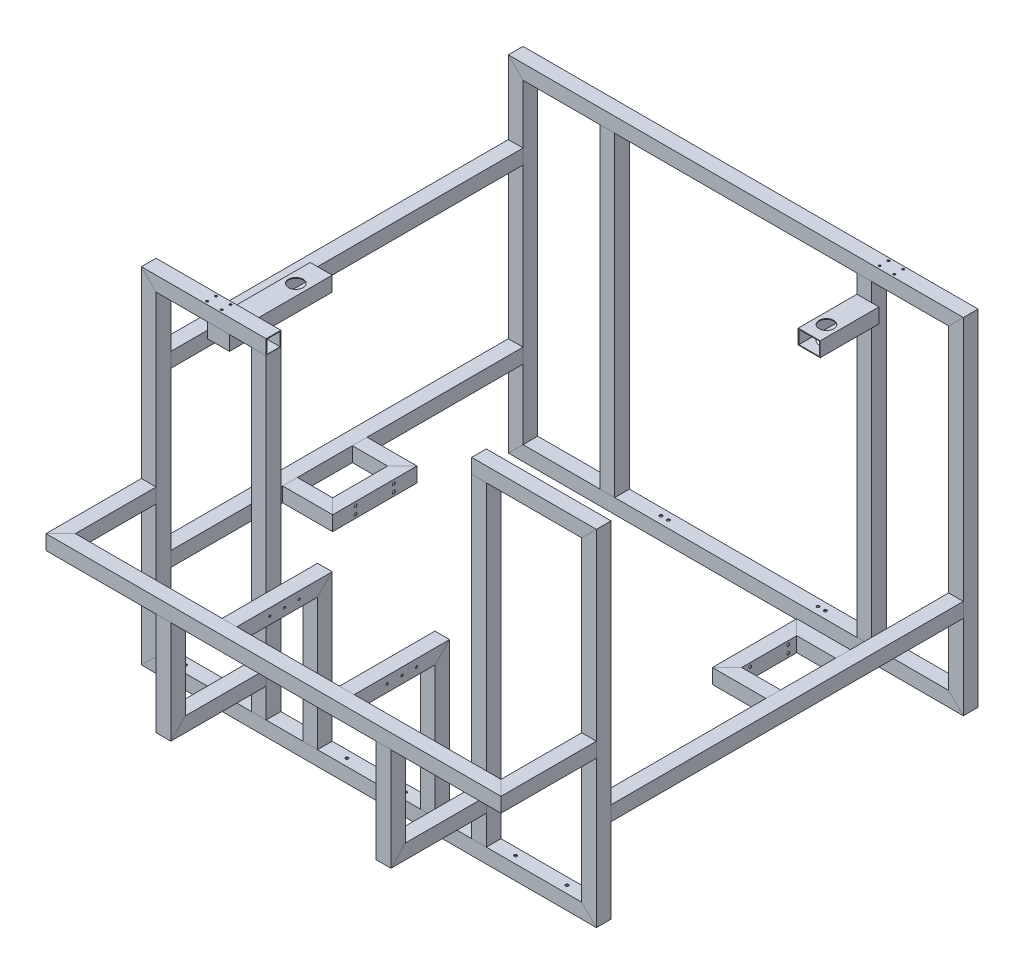
SolidWorks part; units mm, degrees
material "6063-O"
ref_plane "前视基准面" through (0, 0, 0) normal (0, 0, 1) x (1, 0, 0)
ref_plane "上视基准面" through (0, 0, 0) normal (0, 1, 0) x (1, 0, 0)
ref_plane "右视基准面" through (0, 0, 0) normal (1, 0, 0) x (0, 0, -1)
sketch "草图1" plane through (0, 0, 0) normal (0, 0, 1) x (1, 0, 0)
  line L1 (-300, 225) -> (300, 225)
  line L2 (-175, 225) -> (-175, -225)
  line L4 (175, 225) -> (175, -225)
  line L5 (-175, 225) -> (175, -225) construction
  line L6 (-175, -225) -> (175, 225) construction
  line L7 (-300, 225) -> (-300, -225)
  line L10 (300, 225) -> (300, -225)
  line L12 (-300, -225) -> (300, -225)
  point P0 (0, 0)
  dimension "D1" = 350
  dimension "D2" = 450
  dimension "D3" = 125
  dimension "D4" = 125
ref_plane "基准面1" through (0, 0, 500) normal (0, 0, 1) x (1, 0, 0)
sketch "草图2" plane through (0, 0, 500) normal (0, 0, 1) x (1, 0, 0)
  line L2 (300, 225) -> (300, -225) construction
  line L5 (-300, -225) -> (300, -225) construction
  line L6 (-300, 225) -> (-300, -225) construction
  line L7 (-150, 225) -> (-150, -225)
  line L8 (150, 225) -> (150, -225)
  line L14 (-300, 225) -> (300, 225) construction
  line L15 (300, 225) -> (300, -225)
  line L19 (-300, -225) -> (300, -225)
  line L20 (-300, 225) -> (-300, -225)
  line L22 (-300, 225) -> (300, 225)
  dimension "D1" = 150
  dimension "D2" = 150
sketch3d "3D草图1"
  line L0 (-300, -110, 0) -> (-300, -110, 500)
  line L1 (-300, 225, 0) -> (-300, -225, 0) construction
  line L2 (-300, 225, 500) -> (-300, -225, 500) construction
  line L3 (-300, 125, 0) -> (-300, 125, 500)
  line L4 (300, -110, 0) -> (300, -110, 500)
  line L5 (300, 225, 0) -> (300, -225, 0) construction
  line L6 (300, 225, 500) -> (300, -225, 500) construction
  line L8 (-300, -225, 500) -> (300, -225, 500) construction
  line L9 (300, -110, 249) -> (227, -110, 249)
  line L10 (-80, -225, 500) -> (-80, -25, 500)
  line L11 (227, -110, 249) -> (227, -110, 154)
  line L12 (80, -225, 500) -> (80, -25, 500)
  line L13 (227, -110, 154) -> (300, -110, 154)
  line L14 (-300, -110, 327.5) -> (-232, -110, 327.5)
  line L15 (-232, -110, 327.5) -> (-232, -110, 232.5)
  line L16 (-300, -25, 500) -> (-300, -25, 630)
  line L17 (-300, -25, 630) -> (300, -25, 630)
  line L18 (300, -25, 630) -> (300, -25, 500)
  line L19 (-232, -110, 232.5) -> (-300, -110, 232.5)
  line L20 (-80, -25, 630) -> (-80, -25, 500)
  line L21 (80, -25, 630) -> (80, -25, 500)
  dimension "D1" = 115
  dimension "D2" = 100
  dimension "D3" = 115
  dimension "D4" = 154
  dimension "D5" = 249
  dimension "D10" = 267.5
  dimension "D6" = 200
  dimension "D7" = 130
  dimension "D8" = 73
  dimension "D9" = 172.5
  dimension "D11" = 68
  dimension "D12" = 220
  dimension "D13" = 220
other " C:\\PROGRAM FILES\\SOLIDWORKS CORP\\SOLIDWORKS\\LANG\\CHINESE-SIMPLIFIED\\WELDMENT PROFILES\\HITCRT\\新建文件夹\\20X20X1 - 丢失(1)"
ref_plane "基准面2" through (-300, 225, 0) normal (0, -1, 0) x (1, 0, 0)
sketch "草图11" plane through (-300, 225, 0) normal (0, -1, 0) x (1, 0, 0)
  line L1 (-10, -10) -> (10, -10)
  line L2 (-10, -10) -> (-10, 10)
  line L3 (-10, 10) -> (10, 10)
  line L4 (10, -10) -> (10, 10)
  line L5 (-10, -10) -> (10, 10) construction
  line L6 (-10, 10) -> (10, -10) construction
  line L7 (-9, -9) -> (9, -9)
  line L8 (-9, -9) -> (-9, 9)
  line L9 (-9, 9) -> (9, 9)
  line L10 (9, -9) -> (9, 9)
  line L11 (-9, -9) -> (9, 9) construction
  line L12 (-9, 9) -> (9, -9) construction
  point P0 (0, 0)
  point P6 (0, 0)
  point P11 (0, 0)
  dimension "D1" = 20
  dimension "D2" = 20
  dimension "D3" = 18
  dimension "D4" = 18
sketch "草图13" plane through (0, 0, 510) normal (0, 0, 1) x (1, 0, 0)
  line L0 (-310, 235) -> (310, 235) construction
  line L1 (-140, 215) -> (140, 215)
  line L3 (-140, 235) -> (140, 235)
  line L4 (140, 215) -> (140, 235)
  line L5 (-140, 215) -> (-140, 235)
  line L7 (-140, -215) -> (-140, 215) construction
  line L8 (140, -215) -> (140, 215) construction
  dimension "D1" = 0
  dimension "D2" = 0
extrude "切除-拉伸2" cut sketch "草图13" against normal blind 20
sketch "草图14" plane through (-70, 0, 0) normal (1, 0, 0) x (0, 0, -1)
  circle A0 centre (-535, -25) radius 1.5 construction
  circle A1 centre (-555, -25) radius 1.5 construction
  circle A2 centre (-575, -25) radius 1.5 construction
  circle A3 centre (-535, -25) radius 1.5
  circle A4 centre (-555, -25) radius 1.5
  circle A5 centre (-575, -25) radius 1.5
extrude "切除-拉伸3" cut sketch "草图14" against normal blind 20 and the other way blind 230
sketch "草图17" plane through (0, 0, 510) normal (0, 0, 1) x (1, 0, 0)
  line L0 (-290, 215) -> (-140, 215) construction
  line L1 (-190, 215) -> (-220, 215)
  line L2 (-190, 215) -> (-190, 195)
  line L3 (-190, 195) -> (-220, 195)
  line L4 (-220, 215) -> (-220, 195)
  dimension "D1" = 20
  dimension "D2" = 30
extrude "凸台-拉伸3" add sketch "草图17" against normal blind 140 separate body
shell "抽壳1" thickness 1
sketch "草图18" plane through (0, 215, 0) normal (0, 1, 0) x (1, 0, 0)
  circle A0 centre (-205, -404.5) radius 10
  dimension "D1" = 20
extrude "切除-拉伸4" cut sketch "草图18" against normal up to surface (20 mm away) up to face at (-205, 195, 440)
sketch "草图19" plane through (165, 0, 0) normal (-1, 0, 0) x (0, 0, 1)
  line L0 (10, -215) -> (10, 215) construction
  line L1 (10, 190) -> (90, 190)
  line L2 (10, 190) -> (10, 170)
  line L3 (10, 170) -> (90, 170)
  line L4 (90, 190) -> (90, 170)
  dimension "D1" = 20
  dimension "D2" = 80
  dimension "D3" = 25
extrude "凸台-拉伸4" add sketch "草图19" against normal blind 30 separate body
shell "抽壳2" thickness 1
sketch "草图20" plane through (0, 190, 0) normal (0, 1, 0) x (1, 0, 0)
  circle A0 centre (180, -66.5) radius 10
  dimension "D1" = 20
extrude "切除-拉伸5" cut sketch "草图20" against normal up to surface (20 mm away) up to face at (180, 170, 50)
sketch "草图21" plane through (217, 0, 0) normal (-1, 0, 0) x (0, 0, 1)
  line L0 (144, -100) -> (259, -100) construction
  line L1 (144, -100) -> (144, -120) construction
  circle A0 centre (175.5, -105) radius 2
  circle A1 centre (175.5, -115) radius 2
  circle A2 centre (227.5, -105) radius 2
  circle A3 centre (227.5, -115) radius 2
  dimension "D1" = 10
  dimension "D2" = 5
  dimension "D3" = 5
  dimension "D4" = 10
  dimension "D5" = 52
  dimension "D6" = 52
  dimension "D7" = 31.5
  dimension "D8" = 31.5
  dimension "D9" = 4
  dimension "D10" = 4
  dimension "D11" = 4
  dimension "D12" = 4
extrude "切除-拉伸6" cut sketch "草图21" against normal blind 20
sketch "草图22" plane through (-222, 0, 0) normal (1, 0, 0) x (0, 0, -1)
  line L0 (-337.5, -120) -> (-337.5, -100) construction
  line L1 (-337.5, -100) -> (-337.5, -120) construction
  line L2 (-222.5, -100) -> (-337.5, -100) construction
  circle A0 centre (-306, -105) radius 2
  circle A1 centre (-254, -105) radius 2
  circle A2 centre (-254, -115) radius 2
  circle A3 centre (-306, -115) radius 2
  dimension "D1" = 52
  dimension "D2" = 52
  dimension "D3" = 31.5
  dimension "D4" = 31.5
  dimension "D5" = 10
  dimension "D6" = 10
  dimension "D7" = 5
  dimension "D8" = 5
  dimension "D9" = 4
  dimension "D10" = 4
  dimension "D11" = 4
  dimension "D12" = 4
extrude "切除-拉伸7" cut sketch "草图22" against normal blind 20
ref_plane "基准面3" through (-150, 0, 0) normal (-1, 0, 0) x (0, 0, 1)
sketch "草图23" plane through (-150, 0, 0) normal (-1, 0, 0) x (0, 0, 1)
  line L0 (630, -35) -> (630, -165)
  line L1 (630, -165) -> (510, -165)
  line L2 (510, -235) -> (510, 235) construction
  line L3 (640, -35) -> (510, -35) construction
  line L4 (640, -35) -> (640, -15) construction
  dimension "D1" = 130
  dimension "D2" = 10
other "铝管 20X20X1(1)"
ref_plane "基准面4" through (-150, -35, 630) normal (0, -1, 0) x (0, 0, 1)
sketch "草图110" plane through (-150, -35, 630) normal (0, -1, 0) x (0, 0, 1)
  line L1 (-10, -10) -> (10, -10)
  line L2 (-10, -10) -> (-10, 10)
  line L3 (-10, 10) -> (10, 10)
  line L4 (10, -10) -> (10, 10)
  line L5 (-10, -10) -> (10, 10) construction
  line L6 (-10, 10) -> (10, -10) construction
  line L7 (-9, -9) -> (9, -9)
  line L8 (-9, -9) -> (-9, 9)
  line L9 (-9, 9) -> (9, 9)
  line L10 (9, -9) -> (9, 9)
  line L11 (-9, -9) -> (9, 9) construction
  line L12 (-9, 9) -> (9, -9) construction
  point P0 (0, 0)
  point P6 (0, 0)
  point P11 (0, 0)
  dimension "D1" = 20
  dimension "D2" = 20
  dimension "D3" = 18
  dimension "D4" = 18
ref_plane "基准面5" through (150, 0, 0) normal (1, 0, 0) x (0, 0, -1)
sketch "草图111" plane through (150, 0, 0) normal (1, 0, 0) x (0, 0, -1)
  line L0 (-630, -165) -> (-510, -165) construction
  line L1 (-630, -35) -> (-630, -165) construction
  line L2 (-630, -165) -> (-510, -165)
  line L3 (-630, -35) -> (-630, -165)
other "铝管 20X20X1(2)"
ref_plane "基准面6" through (150, -35, 630) normal (0, -1, 0) x (0, 0, -1)
sketch "草图112" plane through (150, -35, 630) normal (0, -1, 0) x (0, 0, -1)
  line L1 (-10, -10) -> (10, -10)
  line L2 (-10, -10) -> (-10, 10)
  line L3 (-10, 10) -> (10, 10)
  line L4 (10, -10) -> (10, 10)
  line L5 (-10, -10) -> (10, 10) construction
  line L6 (-10, 10) -> (10, -10) construction
  line L7 (-9, -9) -> (9, -9)
  line L8 (-9, -9) -> (-9, 9)
  line L9 (-9, 9) -> (9, 9)
  line L10 (9, -9) -> (9, 9)
  line L11 (-9, -9) -> (9, 9) construction
  line L12 (-9, 9) -> (9, -9) construction
  point P0 (0, 0)
  point P6 (0, 0)
  point P11 (0, 0)
  dimension "D1" = 20
  dimension "D2" = 20
  dimension "D3" = 18
  dimension "D4" = 18
sketch "草图113" plane through (0, -215, 0) normal (0, 1, 0) x (1, 0, 0)
  line L0 (290, 10) -> (-290, 10) construction
  line L1 (290, 10) -> (290, -10) construction
  line L2 (0, -10) -> (0, 10)
  line L3 (290, -10) -> (-290, -10) construction
  circle A0 centre (112, 0) radius 2
  circle A1 centre (102, 0) radius 2
  circle A2 centre (-102, 0) radius 2
  circle A3 centre (-112, 0) radius 2
  dimension "D1" = 10
  dimension "D2" = 10
  dimension "D3" = 10
  dimension "D4" = 4
  dimension "D5" = 4
  dimension "D6" = 178
extrude "切除-拉伸8" cut sketch "草图113" against normal blind 20 contours A1 | A0 | A3 | A2
sketch "草图114" plane through (0, -215, 0) normal (0, 1, 0) x (1, 0, 0)
  line L0 (290, -490) -> (-290, -490) construction
  line L1 (-290, -510) -> (-290, -490) construction
  line L2 (-70, -490) -> (-70, -510) construction
  line L3 (0, -510) -> (0, -490)
  line L4 (290, -510) -> (-290, -510) construction
  circle A0 centre (40, -500) radius 2
  circle A1 centre (260, -500) radius 2
  circle A2 centre (190, -500) radius 2
  circle A3 centre (-40, -500) radius 2
  circle A4 centre (-190, -500) radius 2
  circle A5 centre (-260, -500) radius 2
  dimension "D1" = 10
  dimension "D2" = 10
  dimension "D3" = 10
  dimension "D4" = 30
  dimension "D5" = 70
  dimension "D6" = 4
  dimension "D7" = 30
  dimension "D8" = 4
  dimension "D9" = 4
extrude "切除-拉伸9" cut sketch "草图114" against normal through all contours A5 | A4 | A3 | A0 | A2 | A1
sketch "草图115" plane through (0, 235, 0) normal (0, 1, 0) x (1, 0, 0)
  line L0 (-310, -490) -> (-140, -490) construction
  line L1 (-310, -510) -> (-140, -510) construction
  line L2 (-310, 10) -> (310, 10) construction
  line L3 (-310, -10) -> (310, -10) construction
  line L5 (310, -10) -> (310, 10) construction
  line L6 (-310, -510) -> (-310, -490) construction
  circle A0 centre (-224.5, -494) radius 1.5
  circle A1 centre (-224.5, -506) radius 1.5
  circle A2 centre (-204.5, -506) radius 1.5
  circle A3 centre (-204.5, -494) radius 1.5
  circle A4 centre (192, 6) radius 1.5
  circle A5 centre (212, 6) radius 1.5
  circle A6 centre (212, -6) radius 1.5
  circle A7 centre (192, -6) radius 1.5
  dimension "D1" = 20
  dimension "D2" = 20
  dimension "D3" = 12
  dimension "D4" = 12
  dimension "D5" = 4
  dimension "D6" = 4
  dimension "D7" = 4
  dimension "D8" = 3
  dimension "D9" = 3
  dimension "D10" = 3
  dimension "D11" = 3
  dimension "D12" = 12
  dimension "D13" = 12
  dimension "D14" = 4
  dimension "D15" = 4
  dimension "D16" = 20
  dimension "D17" = 20
  dimension "D18" = 4
  dimension "D19" = 3
  dimension "D20" = 3
  dimension "D21" = 3
  dimension "D22" = 3
  dimension "D23" = 98
  dimension "D24" = 85.5
extrude "切除-拉伸10" cut sketch "草图115" against normal blind 20
